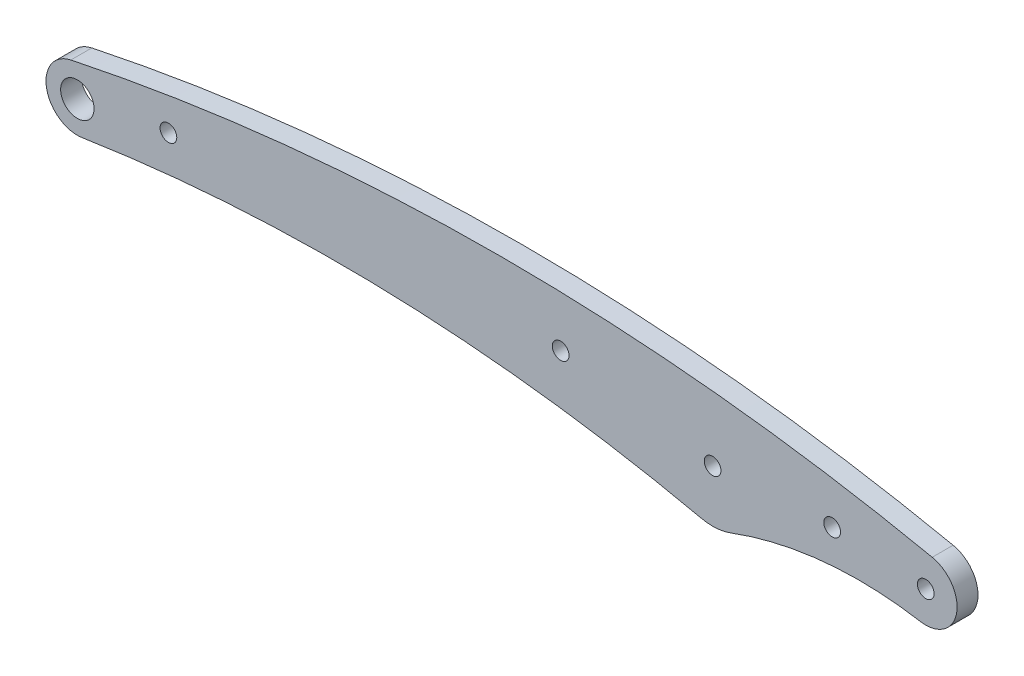
SolidWorks part; units mm, degrees
ref_plane "Piano frontale" through (0, 0, 0) normal (0, 0, 1) x (1, 0, 0)
ref_plane "Piano superiore" through (0, 0, 0) normal (0, 1, 0) x (1, 0, 0)
ref_plane "Piano destro" through (0, 0, 0) normal (1, 0, 0) x (0, 0, -1)
sketch "Schizzo1" plane through (0, 0, 0) normal (0, 0, 1) x (1, 0, 0)
  circle A0 centre (0, 0) radius 4
  circle A1 centre (203, 0) radius 2
  arc A2 (-1.5457, 7.339) -> (1.1505, -7.4112) centre (0, 0) ccw
  arc A3 (201.7422, -7.3938) -> (204.5457, 7.339) centre (203, 0) ccw
  circle A4 centre (152, 0) radius 2
  arc A5 (149.2883, -12.2023) -> (156.3812, -11.707) centre (152, 0) ccw
  arc A6 (149.2883, -12.2023) -> (1.1505, -7.4112) centre (62.5132, -402.6765) ccw
  arc A7 (204.5457, 7.339) -> (-1.5457, 7.339) centre (101.5, -481.9274) ccw
  arc A8 (201.7422, -7.3938) -> (156.3812, -11.707) centre (187.0623, -93.6896) ccw
  dimension "D1" = 8
  dimension "D2" = 4
  dimension "D4" = 15
  dimension "D5" = 15
  dimension "D6" = 4
  dimension "D8" = 25
  dimension "D9" = 800
  dimension "D10" = 1000
  dimension "D3" = 203
  dimension "D7" = 51
extrude "Estrusione-Estrusione1" add sketch "Schizzo1" along normal blind 5
sketch "Schizzo2" plane through (0, 0, 5) normal (0, 0, 1) x (1, 0, 0)
  circle A0 centre (21.7926, 3.9239) radius 2
  circle A1 centre (115.6435, 5.6739) radius 2
  circle A2 centre (180.6026, 1.5866) radius 2
  dimension "D1" = 4
  dimension "D2" = 4
  dimension "D3" = 4
extrude "Taglio-Estrusione1" cut sketch "Schizzo2" against normal blind 10
